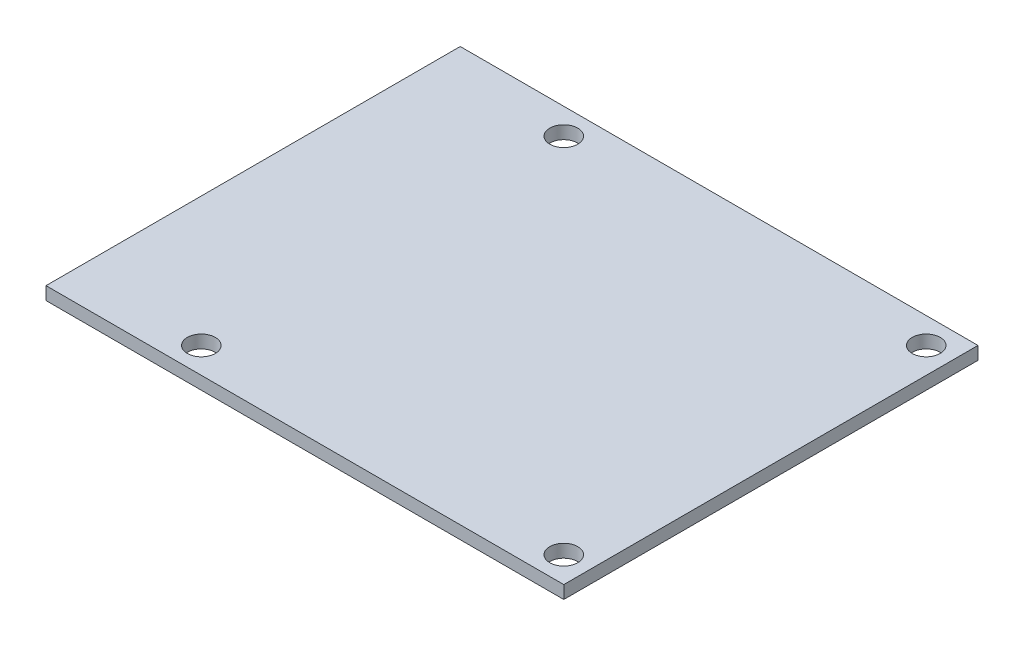
SolidWorks part; units mm, degrees
ref_plane "Front Plane" through (0, 0, 0) normal (0, 0, 1) x (1, 0, 0)
ref_plane "Top Plane" through (0, 0, 0) normal (0, 1, 0) x (1, 0, 0)
ref_plane "Right Plane" through (0, 0, 0) normal (1, 0, 0) x (0, 0, -1)
sketch "Sketch1" plane through (0, 0, 0) normal (0, 1, 0) x (1, 0, 0)
  line L1 (-63.5, -50.8) -> (63.5, -50.8)
  line L2 (-63.5, -50.8) -> (-63.5, 50.8)
  line L3 (-63.5, 50.8) -> (63.5, 50.8)
  line L4 (63.5, -50.8) -> (63.5, 50.8)
  line L5 (-63.5, -50.8) -> (63.5, 50.8) construction
  line L6 (-63.5, 50.8) -> (63.5, -50.8) construction
  point P0 (0, 0)
  dimension "D1" = 101.6
  dimension "D2" = 127
extrude "Boss-Extrude1" add sketch "Sketch1" along normal blind 3.175
sketch "Sketch2" plane through (0, 0, 0) normal (0, -1, 0) x (-1, 0, 0)
  line L0 (-63.5, -50.8) -> (-63.5, 50.8) construction
  line L1 (63.5, -50.8) -> (-63.5, -50.8) construction
  circle A0 centre (-57.15, -44.45) radius 3.429
  circle A1 centre (31.75, -44.45) radius 3.429
  circle A2 centre (31.75, 44.45) radius 3.429
  circle A3 centre (-57.15, 44.45) radius 3.429
  dimension "D1" = 6.858
  dimension "D2" = 6.35
  dimension "D3" = 6.35
  dimension "D4" = 2
  dimension "D5" = 2
extrude "Cut-Extrude1" cut sketch "Sketch2" against normal through all
